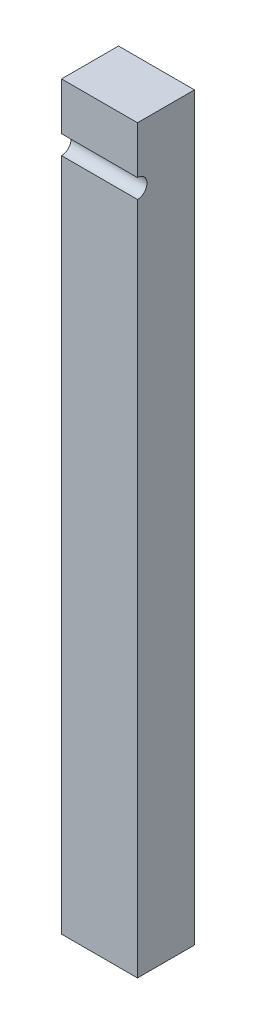
SolidWorks part; units mm, degrees
ref_plane "Front Plane" through (0, 0, 0) normal (0, 0, 1) x (1, 0, 0)
ref_plane "Top Plane" through (0, 0, 0) normal (0, 1, 0) x (1, 0, 0)
ref_plane "Right Plane" through (0, 0, 0) normal (1, 0, 0) x (0, 0, -1)
sketch "Sketch1" plane through (0, 0, 0) normal (0, 1, 0) x (1, 0, 0)
  line L1 (0, 0) -> (101.6, 0)
  line L2 (0, 0) -> (0, 76.2)
  line L3 (0, 76.2) -> (101.6, 76.2)
  line L4 (101.6, 0) -> (101.6, 76.2)
  dimension "D1" = 101.6
  dimension "D2" = 76.2
extrude "Boss-Extrude1" add sketch "Sketch1" along normal blind 990.6
sketch "Sketch2" plane through (101.6, 0, 0) normal (1, 0, 0) x (0, 0, -1)
  line L0 (0, 990.6) -> (76.2, 990.6) construction
  line L1 (76.2, 990.6) -> (76.2, 0) construction
  circle A0 centre (0, 914.4) radius 12.7
  dimension "D1" = 25.4
  dimension "D3" = 76.2
  dimension "D2" = 76.2
extrude "Cut-Extrude1" cut sketch "Sketch2" against normal through all
